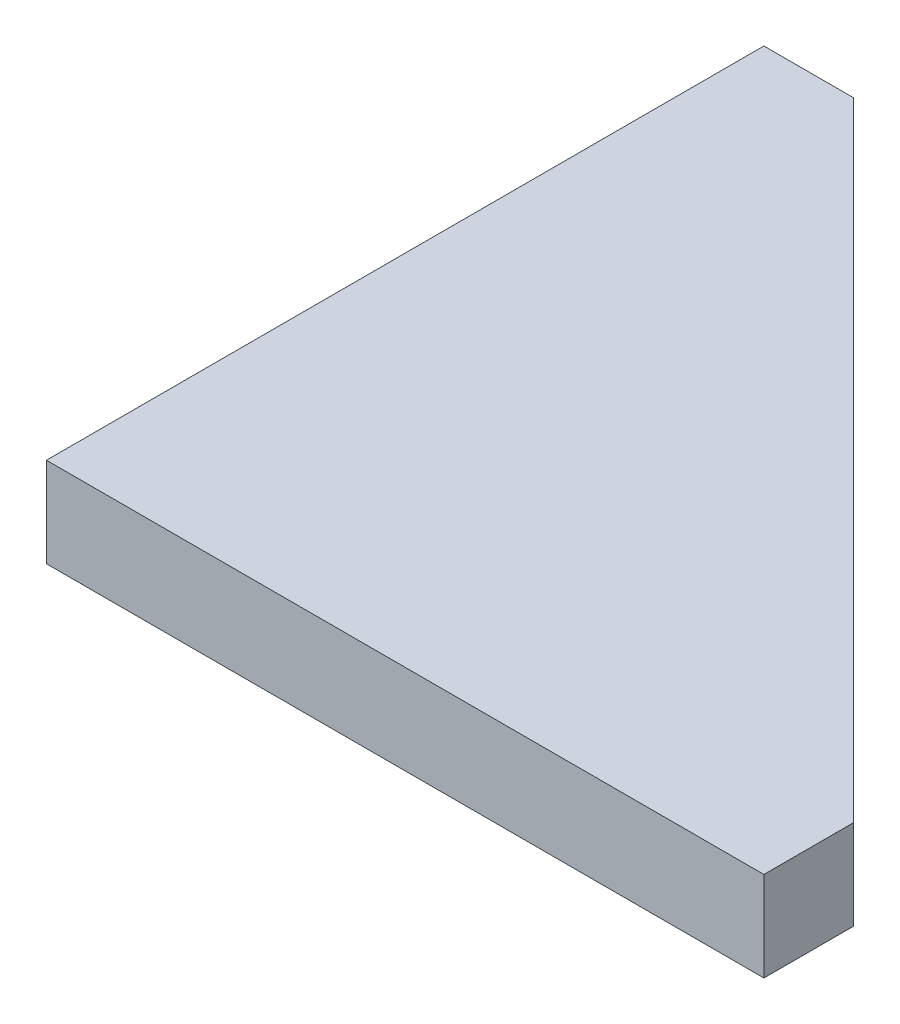
SolidWorks part; units mm, degrees
ref_plane "Alzado" through (0, 0, 0) normal (0, 0, 1) x (1, 0, 0)
ref_plane "Planta" through (0, 0, 0) normal (0, 1, 0) x (1, 0, 0)
ref_plane "Vista lateral" through (0, 0, 0) normal (1, 0, 0) x (0, 0, -1)
sketch "Croquis1" plane through (0, 0, 0) normal (0, 1, 0) x (1, 0, 0)
  line L0 (0, 0) -> (0, 76.2)
  line L1 (0, 0) -> (76.2, 0)
  line L2 (0, 76.2) -> (76.2, 0)
  dimension "D1" = 76.2
  dimension "D2" = 76.2
extrude "Saliente-Extruir1" add sketch "Croquis1" along normal blind 9.525
sketch "Croquis2" plane through (0, 9.525, 0) normal (0, 1, 0) x (1, 0, 0)
  line L0 (76.2, 0) -> (76.2, 9.525)
  line L1 (0, 76.2) -> (9.525, 76.2)
  line L2 (76.2, 9.525) -> (9.525, 76.2)
  line L3 (0, 76.2) -> (76.2, 0)
  dimension "D1" = 9.525
  dimension "D2" = 9.525
extrude "Saliente-Extruir2" add sketch "Croquis2" against normal up to surface (9.525 mm away) up to face at (25.4, 0, -25.4)
